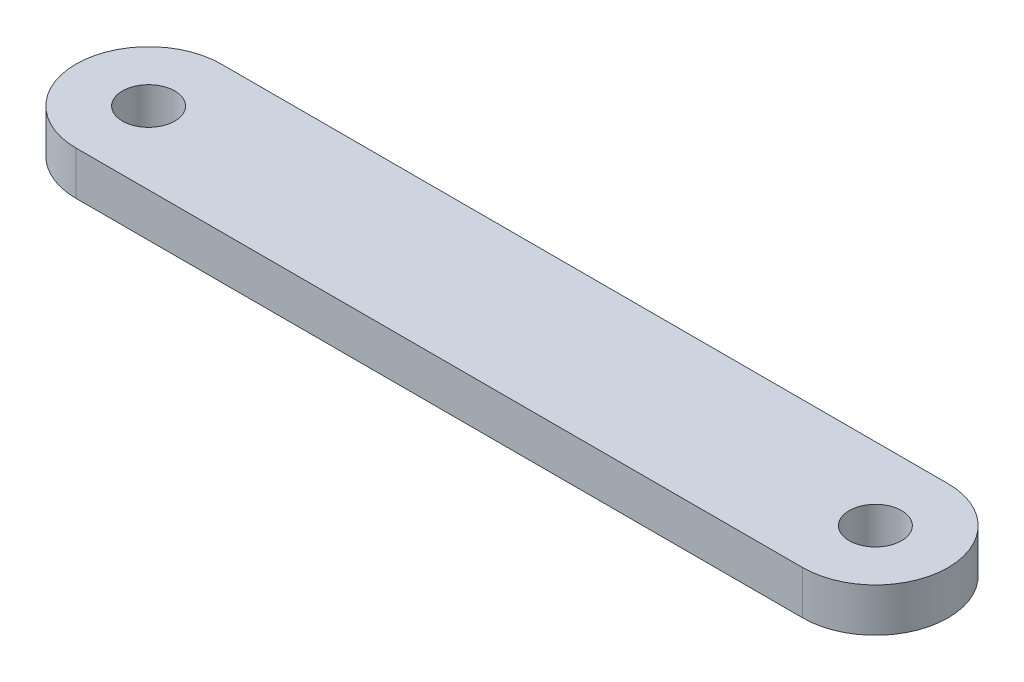
SolidWorks part; units mm, degrees
ref_plane "Front" through (0, 0, 0) normal (0, 0, 1) x (1, 0, 0)
ref_plane "Top" through (0, 0, 0) normal (0, 1, 0) x (1, 0, 0)
ref_plane "Right" through (0, 0, 0) normal (1, 0, 0) x (0, 0, -1)
sketch "草图1" plane through (0, 0, 0) normal (0, 1, 0) x (1, 0, 0)
  line L0 (0, 0) -> (50, 0) construction
  line L1 (0, 5) -> (50, 5)
  line L2 (0, -5) -> (50, -5)
  arc A0 (0, 5) -> (0, -5) centre (0, 0) ccw
  arc A1 (50, -5) -> (50, 5) centre (50, 0) ccw
  circle A2 centre (0, 0) radius 1.8
  circle A3 centre (50, 0) radius 1.8
  point P3 (25, 0)
  dimension "D2" = 5
  dimension "D3" = 3.6
  dimension "D4" = 3.6
  dimension "D1" = 50
extrude "凸台-拉伸1" add sketch "草图1" along normal blind 3
